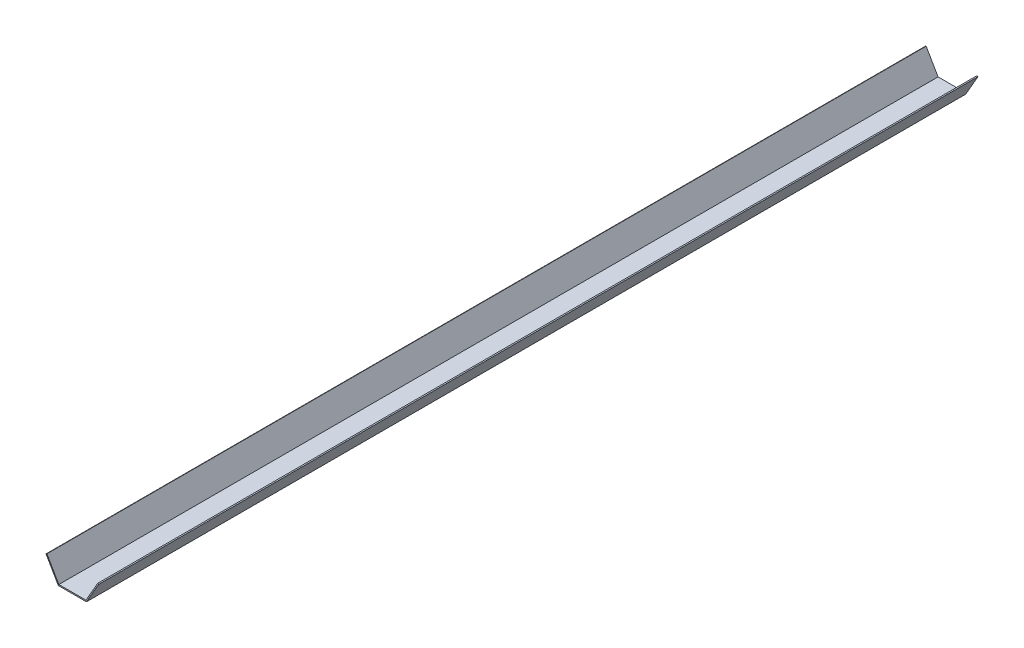
SolidWorks part; units mm, degrees
ref_plane "Спереди" through (0, 0, 0) normal (0, 0, 1) x (1, 0, 0)
ref_plane "Сверху" through (0, 0, 0) normal (0, 1, 0) x (1, 0, 0)
ref_plane "Справа" through (0, 0, 0) normal (1, 0, 0) x (0, 0, -1)
sketch "Эскиз1" plane through (0, 0, 0) normal (0, 0, 1) x (1, 0, 0)
  line L0 (-20, -1.701) -> (20, -1.701)
  line L1 (20, -1.701) -> (37.5, 28.6099)
  line L2 (37.5, 28.6099) -> (36.201, 29.3599)
  line L3 (36.201, 29.3599) -> (19.25, 0)
  line L4 (19.25, 0) -> (-19.25, 0)
  line L5 (-19.25, 0) -> (-36.201, 29.3599)
  line L6 (-37.5, 28.6099) -> (-36.201, 29.3599)
  line L7 (-37.5, 28.6099) -> (-20, -1.701)
  dimension "D1" = 40
  dimension "D2" = 1.5
  dimension "D3" = 120
  dimension "D4" = 35
  dimension "D5" = 38.5
extrude "Бобышка-Вытянуть1" add sketch "Эскиз1" along normal blind 1250
